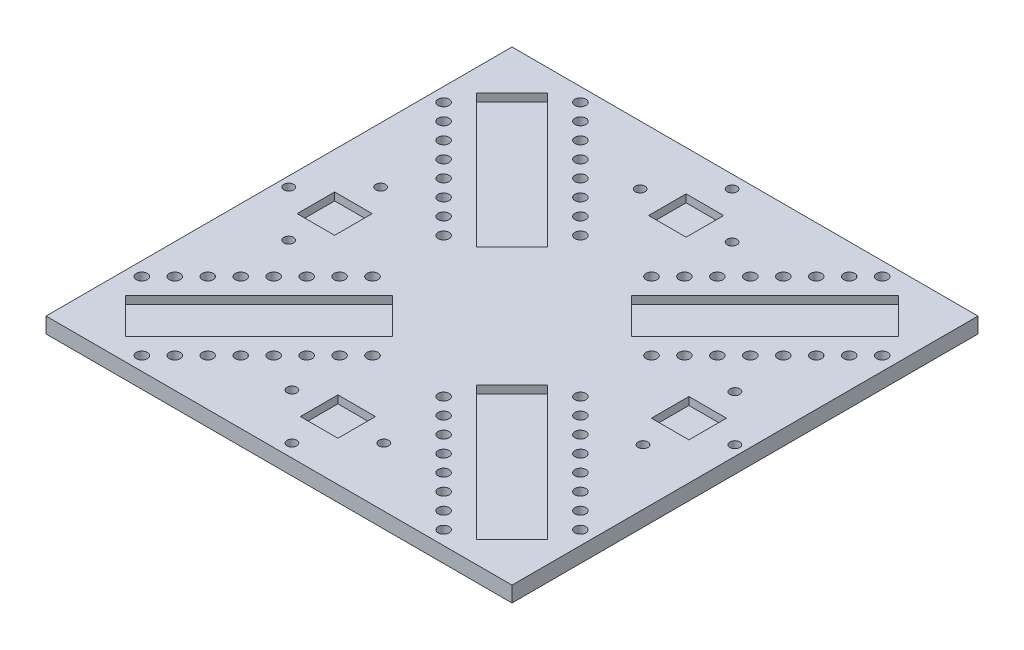
SolidWorks part; units mm, degrees
ref_plane "Front Plane" through (0, 0, 0) normal (0, 0, 1) x (1, 0, 0)
ref_plane "Top Plane" through (0, 0, 0) normal (0, 1, 0) x (1, 0, 0)
ref_plane "Right Plane" through (0, 0, 0) normal (1, 0, 0) x (0, 0, -1)
sketch "Sketch1" plane through (0, 0, 0) normal (0, 0, 1) x (1, 0, 0)
  line L1 (0, 0) -> (381, 0)
  line L2 (0, 0) -> (0, 12.7)
  line L3 (0, 12.7) -> (381, 12.7)
  line L4 (381, 0) -> (381, 12.7)
  dimension "D1" = 12.7
  dimension "D2" = 381
extrude "Boss-Extrude1" add sketch "Sketch1" along normal blind 381
sketch "Sketch2" plane through (0, 12.7, 0) normal (0, 1, 0) x (1, 0, 0)
  line L0 (0, 0) -> (381, -381) construction
  line L1 (381, 0) -> (0, -381) construction
  line L2 (17.9518, -334.0568) -> (46.9432, -363.0482)
  line L3 (17.9518, -334.0568) -> (98.7741, -253.2345)
  line L4 (98.7741, -253.2345) -> (127.7655, -282.2259)
  line L5 (127.7655, -282.2259) -> (46.9432, -363.0482)
  line L6 (98.7741, -253.2345) -> (132.3617, -219.6469) construction
  line L7 (132.3617, -219.6469) -> (161.3531, -248.6383) construction
  line L8 (161.3531, -248.6383) -> (127.7655, -282.2259) construction
  line L21 (46.9432, -363.0482) -> (73.8839, -389.989) construction
  line L22 (190.5, 0) -> (190.5, -381) construction
  line L23 (381, 0) -> (0, 0) construction
  line L24 (381, -381) -> (0, -381) construction
  line L25 (0, -190.5) -> (381, -190.5) construction
  line L26 (0, -381) -> (0, 0) construction
  line L27 (381, -381) -> (381, 0) construction
  line L28 (282.2259, -253.2345) -> (253.2345, -282.2259)
  line L29 (363.0482, -334.0568) -> (282.2259, -253.2345)
  line L30 (363.0482, -334.0568) -> (334.0568, -363.0482)
  line L31 (253.2345, -282.2259) -> (334.0568, -363.0482)
  line L32 (363.0482, -46.9432) -> (282.2259, -127.7655)
  line L33 (363.0482, -46.9432) -> (334.0568, -17.9518)
  line L34 (253.2345, -98.7741) -> (334.0568, -17.9518)
  line L35 (282.2259, -127.7655) -> (253.2345, -98.7741)
  line L36 (98.7741, -127.7655) -> (127.7655, -98.7741)
  line L37 (17.9518, -46.9432) -> (98.7741, -127.7655)
  line L38 (17.9518, -46.9432) -> (46.9432, -17.9518)
  line L39 (127.7655, -98.7741) -> (46.9432, -17.9518)
  line L41 (0, -175.5) -> (381, -175.5) construction
  line L42 (0, -175.5) -> (0, -205.5) construction
  line L43 (0, -205.5) -> (381, -205.5) construction
  line L44 (381, -175.5) -> (381, -205.5) construction
  line L45 (0, -175.5) -> (381, -205.5) construction
  line L46 (0, -205.5) -> (381, -175.5) construction
  line L47 (175.5, -381) -> (205.5, -381) construction
  line L48 (175.5, -381) -> (175.5, 0) construction
  line L49 (175.5, 0) -> (205.5, 0) construction
  line L50 (205.5, -381) -> (205.5, 0) construction
  line L51 (175.5, -381) -> (205.5, 0) construction
  line L52 (175.5, 0) -> (205.5, -381) construction
  point P8 (190.5, -190.5)
  point P11 (32.4475, -348.5525)
  point P41 (190.5, -190.5)
  point P46 (190.5, -190.5)
  dimension "D6" = 38.1
  dimension "D1" = 41
  dimension "D2" = 114.3
  dimension "D3" = 109.22
  dimension "D4" = 47.5
  dimension "D5" = 30
  dimension "D7" = 30
extrude "Cut-Extrude1" cut sketch "Sketch2" against normal blind 6.35
sketch "Sketch3" plane through (0, 12.7, 0) normal (0, 1, 0) x (1, 0, 0)
  line L0 (127.7655, -282.2259) -> (150.2161, -304.6765) construction
  line L1 (150.2161, -304.6765) -> (123.2754, -331.6173) construction
  line L2 (123.2754, -331.6173) -> (100.8247, -309.1667) construction
  line L3 (46.9432, -363.0482) -> (127.7655, -282.2259) construction
  line L4 (136.7457, -318.1469) -> (114.2951, -295.6963) construction
  line L5 (46.9432, -363.0482) -> (127.7655, -282.2259) construction
  line L6 (105.3148, -313.6568) -> (118.7852, -300.1864) construction
  line L7 (118.7852, -300.1864) -> (132.2556, -286.716) construction
  line L8 (125.5204, -293.4512) -> (143.4809, -311.4117) construction
  line L9 (112.05, -306.9216) -> (130.0106, -324.8821) construction
  line L10 (69.3938, -385.4988) -> (123.2754, -331.6173) construction
  line L11 (73.8839, -336.1074) -> (96.3346, -358.5581) construction
  line L12 (85.1093, -333.8624) -> (103.0698, -351.8229) construction
  line L13 (91.8445, -327.1272) -> (64.9037, -354.0679) construction
  line L14 (109.805, -345.0877) -> (87.3543, -322.637) construction
  line L15 (98.5797, -320.392) -> (116.5402, -338.3525) construction
  line L16 (105.3148, -313.6568) -> (91.8445, -327.1272) construction
  line L17 (69.3938, -385.4988) -> (46.9432, -363.0482) construction
  line L18 (58.1685, -360.8031) -> (76.129, -378.7636) construction
  line L19 (51.4333, -367.5383) -> (64.9037, -354.0679) construction
  line L20 (82.8642, -372.0285) -> (60.4136, -349.5778) construction
  line L21 (71.6389, -347.3327) -> (89.5994, -365.2933) construction
  line L22 (32.4475, -348.5525) -> (113.2698, -267.7302) construction
  line L23 (17.9518, -334.0568) -> (46.9432, -363.0482) construction
  line L24 (127.7655, -282.2259) -> (98.7741, -253.2345) construction
  line L25 (381, 0) -> (0, -381) construction
  line L26 (190.5, 0) -> (190.5, -381) construction
  line L27 (381, 0) -> (0, 0) construction
  line L28 (381, -381) -> (0, -381) construction
  line L29 (0, -190.5) -> (381, -190.5) construction
  line L30 (0, -381) -> (0, 0) construction
  line L31 (381, -381) -> (381, 0) construction
  circle A1 centre (121.0303, -315.9019) radius 4.5
  circle A3 centre (107.5599, -329.3722) radius 4.5
  circle A4 centre (67.1488, -369.7834) radius 4.5
  circle A48 centre (134.5007, -302.4315) radius 4.5
  circle A53 centre (80.6191, -356.313) radius 4.5
  circle A55 centre (94.0895, -342.8426) radius 4.5
  circle A56 centre (11.2166, -313.8512) radius 4.5
  circle A57 centre (24.687, -300.3809) radius 4.5
  circle A58 centre (38.1574, -286.9105) radius 4.5
  circle A59 centre (51.6278, -273.4401) radius 4.5
  circle A60 centre (65.0981, -259.9697) radius 4.5
  circle A61 centre (78.5685, -246.4993) radius 4.5
  circle A62 centre (246.4993, -302.4315) radius 4.5
  circle A63 centre (259.9697, -315.9019) radius 4.5
  circle A64 centre (273.4401, -329.3722) radius 4.5
  circle A65 centre (286.9105, -342.8426) radius 4.5
  circle A66 centre (300.3809, -356.313) radius 4.5
  circle A67 centre (313.8512, -369.7834) radius 4.5
  circle A68 centre (369.7834, -313.8512) radius 4.5
  circle A69 centre (302.4315, -246.4993) radius 4.5
  circle A70 centre (315.9019, -259.9697) radius 4.5
  circle A71 centre (329.3722, -273.4401) radius 4.5
  circle A72 centre (342.8426, -286.9105) radius 4.5
  circle A73 centre (356.313, -300.3809) radius 4.5
  circle A74 centre (134.5007, -78.5685) radius 4.5
  circle A75 centre (121.0303, -65.0981) radius 4.5
  circle A76 centre (107.5599, -51.6278) radius 4.5
  circle A77 centre (94.0895, -38.1574) radius 4.5
  circle A78 centre (80.6191, -24.687) radius 4.5
  circle A79 centre (67.1488, -11.2166) radius 4.5
  circle A80 centre (78.5685, -134.5007) radius 4.5
  circle A81 centre (65.0981, -121.0303) radius 4.5
  circle A82 centre (51.6278, -107.5599) radius 4.5
  circle A83 centre (38.1574, -94.0895) radius 4.5
  circle A84 centre (24.687, -80.6191) radius 4.5
  circle A85 centre (11.2166, -67.1488) radius 4.5
  circle A86 centre (356.313, -80.6191) radius 4.5
  circle A87 centre (342.8426, -94.0895) radius 4.5
  circle A88 centre (329.3722, -107.5599) radius 4.5
  circle A89 centre (315.9019, -121.0303) radius 4.5
  circle A90 centre (302.4315, -134.5007) radius 4.5
  circle A91 centre (369.7834, -67.1488) radius 4.5
  circle A92 centre (313.8512, -11.2166) radius 4.5
  circle A93 centre (300.3809, -24.687) radius 4.5
  circle A94 centre (286.9105, -38.1574) radius 4.5
  circle A95 centre (273.4401, -51.6278) radius 4.5
  circle A96 centre (259.9697, -65.0981) radius 4.5
  circle A97 centre (246.4993, -78.5685) radius 4.5
  point P50 (78.3741, -340.5976)
  dimension "D6" = 9
  dimension "D1" = 31.75
  dimension "D2" = 38.1
  dimension "D5" = 6.35
extrude "Cut-Extrude2" cut sketch "Sketch3" against normal through all
sketch "Sketch4" plane through (0, 12.7, 0) normal (0, 1, 0) x (1, 0, 0)
  line L0 (381, 0) -> (0, -381) construction
  line L1 (319.8, -190.5) -> (350.5, -190.5) construction
  line L3 (319.8, -205.85) -> (350.5, -205.85)
  line L4 (319.8, -205.85) -> (319.8, -175.15)
  line L5 (319.8, -175.15) -> (350.5, -175.15)
  line L6 (350.5, -205.85) -> (350.5, -175.15)
  line L18 (190.5, 0) -> (190.5, -381) construction
  line L19 (190.5, -32.8) -> (190.5, -63.5) construction
  line L20 (0, -175.5) -> (381, -175.5) construction
  line L25 (319.8, -163) -> (319.8, -218) construction
  line L26 (319.8, -175.15) -> (350.5, -175.15) construction
  line L27 (319.8, -175.15) -> (319.8, -149.75) construction
  line L28 (319.8, -149.75) -> (350.5, -149.75) construction
  line L29 (350.5, -175.15) -> (350.5, -149.75) construction
  line L30 (319.8, -163) -> (286.3077, -163) construction
  line L31 (381, 0) -> (0, 0) construction
  line L32 (248.3929, -132.6071) -> (283.7482, -167.9625) construction
  line L33 (0, -175.5) -> (0, -205.5) construction
  line L34 (0, 0) -> (381, -381) construction
  line L35 (267.7302, -267.7302) -> (303.0855, -232.3749) construction
  line L36 (282.2259, -253.2345) -> (253.2345, -282.2259) construction
  line L37 (0, -190.5) -> (381, -190.5) construction
  line L38 (175.15, -63.5) -> (205.85, -63.5)
  line L39 (175.15, -63.5) -> (175.15, -32.8)
  line L40 (175.15, -32.8) -> (205.85, -32.8)
  line L41 (205.85, -63.5) -> (205.85, -32.8)
  line L42 (175.15, -63.5) -> (205.85, -32.8) construction
  line L43 (175.15, -32.8) -> (205.85, -63.5) construction
  line L44 (0, -381) -> (0, 0) construction
  line L45 (381, -381) -> (381, 0) construction
  line L46 (175.15, -348.2) -> (205.85, -348.2)
  line L47 (205.85, -317.5) -> (205.85, -348.2)
  line L48 (175.15, -317.5) -> (205.85, -317.5)
  line L49 (175.15, -317.5) -> (175.15, -348.2)
  line L51 (0, -205.5) -> (381, -205.5) construction
  line L53 (30.15, -205.85) -> (60.85, -205.85)
  line L54 (30.15, -205.85) -> (30.15, -175.15)
  line L55 (30.15, -175.15) -> (60.85, -175.15)
  line L56 (60.85, -205.85) -> (60.85, -175.15)
  line L57 (30.15, -205.85) -> (60.85, -175.15) construction
  line L58 (30.15, -175.15) -> (60.85, -205.85) construction
  line L63 (175.5, -381) -> (205.5, -381) construction
  line L64 (381, -175.5) -> (381, -205.5) construction
  line L65 (0, -175.5) -> (381, -205.5) construction
  line L66 (0, -205.5) -> (381, -175.5) construction
  line L67 (175.5, -381) -> (175.5, 0) construction
  line L68 (175.5, 0) -> (205.5, 0) construction
  line L69 (205.5, -381) -> (205.5, 0) construction
  line L70 (175.5, -381) -> (205.5, 0) construction
  line L71 (175.5, 0) -> (205.5, -381) construction
  circle A0 centre (286.4997, -167.3311) radius 4 construction
  circle A1 centre (286.4997, -167.3311) radius 7 construction
  point P4 (190.5, -190.5)
  point P10 (45.5, -190.5)
  point P15 (190.5, -190.5)
  point P25 (190.5, -190.5)
  point P27 (319.8, -190.5)
  dimension "D1" = 8
  dimension "D8" = 14
  dimension "D14" = 30.7
  dimension "D2" = 30.7
  dimension "D3" = 30.7
  dimension "D4" = 25.4
  dimension "D5" = 55
  dimension "D6" = 50
  dimension "D7" = 50
  dimension "D9" = 30
  dimension "D10" = 30.7
  dimension "D11" = 30.7
  dimension "D12" = 127
  dimension "D13" = 114.3
  dimension "D15" = 30.7
extrude "Cut-Extrude3" cut sketch "Sketch4" against normal blind 6.35
sketch "Sketch5" plane through (0, 12.7, 0) normal (0, 1, 0) x (1, 0, 0)
  line L0 (319.8, -175.15) -> (319.8, -137.05) construction
  line L1 (350.5, -175.15) -> (350.5, -137.05) construction
  line L2 (350.5, -137.05) -> (319.8, -137.05) construction
  line L3 (319.8, -168.8) -> (350.5, -168.8) construction
  line L4 (335.15, -168.8) -> (335.15, -137.05) construction
  line L5 (350.5, -175.15) -> (319.8, -175.15) construction
  line L6 (319.8, -190.5) -> (350.5, -190.5) construction
  line L7 (319.8, -175.15) -> (319.8, -205.85) construction
  line L8 (350.5, -205.85) -> (350.5, -175.15) construction
  line L9 (381, 0) -> (0, -381) construction
  line L10 (190.5, 0) -> (190.5, -381) construction
  line L11 (381, 0) -> (0, 0) construction
  line L12 (381, -381) -> (0, -381) construction
  line L13 (0, -190.5) -> (381, -190.5) construction
  line L14 (0, -381) -> (0, 0) construction
  line L15 (381, -381) -> (381, 0) construction
  line L16 (205.85, -32.8) -> (243.95, -32.8) construction
  line L17 (205.85, -63.5) -> (243.95, -63.5) construction
  line L18 (243.95, -63.5) -> (243.95, -32.8) construction
  line L19 (295.9248, -114.0666) -> (321.8609, -141.9759) construction
  line L20 (282.2259, -127.7655) -> (363.0482, -46.9432) construction
  line L21 (212.2, -32.8) -> (212.2, -63.5) construction
  line L22 (205.85, -63.5) -> (205.85, -32.8) construction
  line L23 (212.2, -48.15) -> (243.95, -48.15) construction
  line L24 (350.5, -175.15) -> (388.6, -175.15) construction
  line L25 (350.5, -205.85) -> (388.6, -205.85) construction
  line L26 (388.6, -205.85) -> (388.6, -175.15) construction
  line L27 (356.85, -175.15) -> (356.85, -205.85) construction
  line L28 (356.85, -190.5) -> (388.6, -190.5) construction
  line L29 (388.6, -190.5) -> (372.725, -190.5) construction
  line L30 (372.725, -190.5) -> (372.725, -175.15) construction
  line L31 (175.15, -32.8) -> (175.15, 5.3) construction
  line L32 (205.85, -32.8) -> (205.85, 5.3) construction
  line L33 (205.85, 5.3) -> (175.15, 5.3) construction
  line L34 (175.15, -26.45) -> (205.85, -26.45) construction
  line L35 (205.85, -32.8) -> (175.15, -32.8) construction
  line L36 (190.5, -26.45) -> (190.5, 5.3) construction
  line L37 (190.5, 5.3) -> (190.5, -10.575) construction
  line L38 (190.5, -10.575) -> (175.15, -10.575) construction
  line L39 (30.15, -175.15) -> (30.15, -137.05) construction
  line L40 (60.85, -175.15) -> (60.85, -137.05) construction
  line L41 (60.85, -137.05) -> (30.15, -137.05) construction
  line L42 (60.85, -175.15) -> (30.15, -175.15) construction
  line L43 (30.15, -168.8) -> (60.85, -168.8) construction
  line L44 (60.85, -175.15) -> (30.15, -175.15) construction
  line L45 (45.5, -168.8) -> (45.5, -137.05) construction
  line L46 (45.5, -137.05) -> (45.5, -152.925) construction
  line L47 (45.5, -152.925) -> (30.15, -152.925) construction
  line L48 (30.15, -205.85) -> (-7.95, -205.85) construction
  line L49 (30.15, -175.15) -> (-7.95, -175.15) construction
  line L50 (-7.95, -175.15) -> (-7.95, -205.85) construction
  line L51 (30.15, -175.15) -> (30.15, -205.85) construction
  line L52 (23.8, -205.85) -> (23.8, -175.15) construction
  line L53 (23.8, -190.5) -> (-7.95, -190.5) construction
  line L54 (-7.95, -190.5) -> (7.925, -190.5) construction
  line L55 (7.925, -190.5) -> (7.925, -205.85) construction
  line L56 (264.7575, -87.2512) -> (237.8167, -60.3104) construction
  line L57 (334.0568, -17.9518) -> (253.2345, -98.7741) construction
  line L58 (321.8609, -141.9759) -> (307.5726, -155.254) construction
  circle A0 centre (335.15, -152.925) radius 4
  circle A3 centre (335.15, -152.925) radius 7 construction
  circle A4 centre (335.15, -228.075) radius 4
  circle A8 centre (228.075, -48.15) radius 4
  circle A9 centre (152.925, -48.15) radius 4
  circle A10 centre (372.725, -190.5) radius 4
  circle A12 centre (190.5, -10.575) radius 4
  circle A13 centre (228.075, -332.85) radius 4
  circle A14 centre (152.925, -332.85) radius 4
  circle A15 centre (190.5, -370.425) radius 4
  circle A16 centre (45.5, -152.925) radius 4
  circle A17 centre (7.925, -190.5) radius 4
  circle A18 centre (45.5, -228.075) radius 4
  point P26 (190.5, -190.5)
  dimension "D3" = 8
  dimension "D4" = 14
  dimension "D5" = 38.1
  dimension "D7" = 8
  dimension "D10" = 8
  dimension "D13" = 8
  dimension "D16" = 8
  dimension "D19" = 8
  dimension "D1" = 38.1
  dimension "D2" = 6.35
  dimension "D6" = 6.35
  dimension "D8" = 38.1
  dimension "D9" = 6.35
  dimension "D11" = 38.1
  dimension "D12" = 6.35
  dimension "D14" = 38.1
  dimension "D15" = 6.35
  dimension "D17" = 38.1
  dimension "D18" = 6.35
  dimension "D20" = 38.1
  dimension "D21" = 38.1
extrude "Cut-Extrude4" cut sketch "Sketch5" against normal through all
sketch "Sketch6" plane through (0, 12.7, 0) normal (0, 1, 0) x (1, 0, 0)
  line L0 (190.5, 0) -> (190.5, -381) construction
  line L1 (381, 0) -> (0, 0) construction
  line L2 (381, -381) -> (0, -381) construction
  line L3 (0, -190.5) -> (381, -190.5) construction
  line L4 (0, -381) -> (0, 0) construction
  line L5 (381, -381) -> (381, 0) construction
  line L6 (98.7741, -253.2345) -> (127.0584, -224.9502)
  line L7 (0, -205.5) -> (381, -205.5) construction
  line L8 (0, -205.5) -> (0, -175.5) construction
  line L9 (0, -175.5) -> (381, -175.5) construction
  line L10 (381, -205.5) -> (381, -175.5) construction
  line L11 (0, -205.5) -> (381, -175.5) construction
  line L12 (0, -175.5) -> (381, -205.5) construction
  line L13 (175.5, -381) -> (205.5, -381) construction
  line L14 (175.5, -381) -> (175.5, 0) construction
  line L15 (175.5, 0) -> (205.5, 0) construction
  line L16 (205.5, -381) -> (205.5, 0) construction
  line L17 (175.5, -381) -> (205.5, 0) construction
  line L18 (175.5, 0) -> (205.5, -381) construction
  line L19 (127.7655, -282.2259) -> (156.0498, -253.9416)
  line L20 (127.7655, -282.2259) -> (98.7741, -253.2345) construction
  line L21 (127.0584, -224.9502) -> (156.0498, -253.9416)
  line L22 (127.0584, -224.9502) -> (151.8071, -200.2015) construction
  line L23 (98.7741, -253.2345) -> (127.7655, -282.2259)
  line L24 (282.2259, -253.2345) -> (253.9416, -224.9502)
  line L25 (253.9416, -224.9502) -> (224.9502, -253.9416)
  line L26 (253.2345, -282.2259) -> (224.9502, -253.9416)
  line L27 (282.2259, -253.2345) -> (253.2345, -282.2259)
  line L28 (282.2259, -127.7655) -> (253.2345, -98.7741)
  line L29 (253.2345, -98.7741) -> (224.9502, -127.0584)
  line L30 (253.9416, -156.0498) -> (224.9502, -127.0584)
  line L31 (282.2259, -127.7655) -> (253.9416, -156.0498)
  line L32 (98.7741, -127.7655) -> (127.0584, -156.0498)
  line L33 (127.0584, -156.0498) -> (156.0498, -127.0584)
  line L34 (127.7655, -98.7741) -> (156.0498, -127.0584)
  line L35 (98.7741, -127.7655) -> (127.7655, -98.7741)
  line L36 (134.5007, -302.4315) -> (121.0303, -288.9611) construction
  line L37 (46.9432, -363.0482) -> (127.7655, -282.2259) construction
  line L38 (121.0303, -315.9019) -> (107.5599, -302.4315) construction
  line L39 (121.0303, -315.9019) -> (134.5007, -302.4315) construction
  line L40 (127.7655, -309.1667) -> (114.2951, -295.6963) construction
  line L41 (127.7655, -282.2259) -> (141.2359, -295.6963) construction
  line L42 (134.5007, -302.4315) -> (141.2359, -295.6963) construction
  line L43 (107.5599, -329.3722) -> (94.0895, -315.9019) construction
  line L44 (46.9432, -363.0482) -> (127.7655, -282.2259) construction
  line L45 (107.5599, -329.3722) -> (121.0303, -315.9019) construction
  line L46 (114.2951, -322.637) -> (100.8247, -309.1667) construction
  line L47 (94.0895, -342.8426) -> (80.6191, -329.3722) construction
  line L48 (94.0895, -342.8426) -> (107.5599, -329.3722) construction
  line L49 (100.8247, -336.1074) -> (87.3543, -322.637) construction
  line L50 (155.0735, -190.1762) -> (190.4288, -154.8208) construction
  line L51 (190.4288, -225.5315) -> (225.7842, -190.1762) construction
  line L52 (190.4288, -154.8208) -> (225.7842, -190.1762) construction
  line L53 (155.0735, -190.1762) -> (190.4288, -225.5315) construction
  line L54 (32.4475, -348.5525) -> (141.5541, -239.4459) construction
  line L55 (17.9518, -334.0568) -> (46.9432, -363.0482) construction
  circle A0 centre (134.5007, -302.4315) radius 4.5 construction
  circle A1 centre (121.0303, -315.9019) radius 4.5 construction
  circle A2 centre (147.9711, -288.9611) radius 4.5
  circle A3 centre (161.4414, -275.4907) radius 4.5
  circle A4 centre (105.5093, -219.5586) radius 4.5
  circle A5 centre (92.0389, -233.0289) radius 4.5
  circle A6 centre (219.5586, -275.4907) radius 4.5
  circle A7 centre (233.0289, -288.9611) radius 4.5
  circle A8 centre (275.4907, -219.5586) radius 4.5
  circle A9 centre (288.9611, -233.0289) radius 4.5
  circle A10 centre (275.4907, -161.4414) radius 4.5
  circle A11 centre (288.9611, -147.9711) radius 4.5
  circle A12 centre (233.0289, -92.0389) radius 4.5
  circle A13 centre (219.5586, -105.5093) radius 4.5
  circle A14 centre (161.4414, -105.5093) radius 4.5
  circle A15 centre (147.9711, -92.0389) radius 4.5
  circle A16 centre (105.5093, -161.4414) radius 4.5
  circle A17 centre (92.0389, -147.9711) radius 4.5
  point P12 (190.5, -190.5)
  point P17 (190.5, -190.5)
  dimension "D7" = 9
  dimension "D1" = 30
  dimension "D2" = 30
  dimension "D3" = 40
  dimension "D4" = 40
  dimension "D5" = 35
  dimension "D6" = 38.1
  dimension "D8" = 50
  dimension "D9" = 50
extrude "Cut-Extrude5" cut sketch "Sketch6" against normal blind 6.35
sketch "Sketch8" plane through (0, 12.7, 0) normal (0, 1, 0) x (1, 0, 0)
  line L1 (190.5, 0) -> (190.5, -381) construction
  line L2 (381, 0) -> (0, 0) construction
  line L3 (381, -381) -> (0, -381) construction
  line L4 (0, -190.5) -> (381, -190.5) construction
  line L5 (0, -381) -> (0, 0) construction
  line L6 (381, -381) -> (381, 0) construction
  circle A0 centre (161.4414, -275.4907) radius 4.5
  circle A1 centre (147.9711, -288.9611) radius 4.5
  circle A2 centre (105.5093, -219.5586) radius 4.5
  circle A3 centre (92.0389, -233.0289) radius 4.5
  circle A4 centre (233.0289, -288.9611) radius 4.5
  circle A5 centre (219.5586, -275.4907) radius 4.5
  circle A6 centre (275.4907, -219.5586) radius 4.5
  circle A7 centre (288.9611, -233.0289) radius 4.5
  circle A8 centre (288.9611, -147.9711) radius 4.5
  circle A9 centre (275.4907, -161.4414) radius 4.5
  circle A10 centre (219.5586, -105.5093) radius 4.5
  circle A11 centre (233.0289, -92.0389) radius 4.5
  circle A12 centre (92.0389, -147.9711) radius 4.5
  circle A13 centre (105.5093, -161.4414) radius 4.5
  circle A14 centre (147.9711, -92.0389) radius 4.5
  circle A15 centre (161.4414, -105.5093) radius 4.5
  dimension "D1" = 9
  dimension "D2" = 9
  dimension "D3" = 9
  dimension "D4" = 9
extrude "Cut-Extrude6" cut sketch "Sketch8" against normal through all
